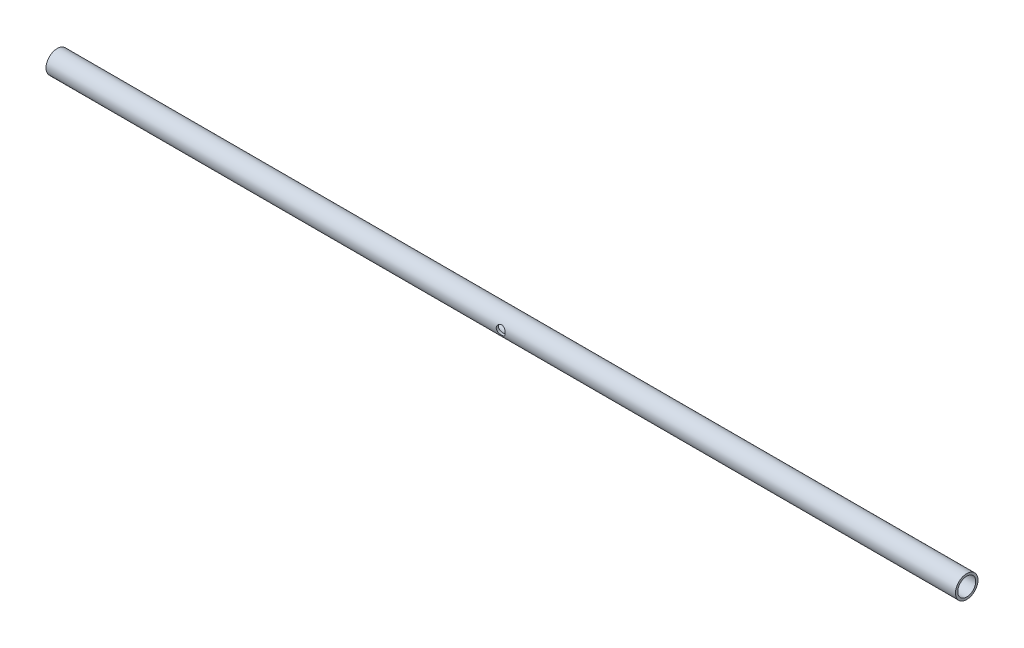
SolidWorks part; units mm, degrees
material "Hexcel AS4C (3000 Filaments)"
ref_plane "前基準面" through (0, 0, 0) normal (0, 0, 1) x (1, 0, 0)
ref_plane "上基準面" through (0, 0, 0) normal (0, 1, 0) x (1, 0, 0)
ref_plane "右基準面" through (0, 0, 0) normal (1, 0, 0) x (0, 0, -1)
sketch "草圖1" plane through (0, 0, 0) normal (1, 0, 0) x (0, 0, -1)
  circle A0 centre (0, 0) radius 5
  circle A1 centre (0, 0) radius 4
  dimension "D1" = 10
  dimension "D2" = 1
extrude "填料-伸長1" add sketch "草圖1" along normal mid plane 403.95
sketch "草圖2" plane through (0, 0, 0) normal (0, 0, 1) x (1, 0, 0)
  circle A0 centre (0, 0) radius 2
  dimension "D1" = 4
extrude "除料-伸長1" cut sketch "草圖2" against normal through all both and the other way through all contours A0
